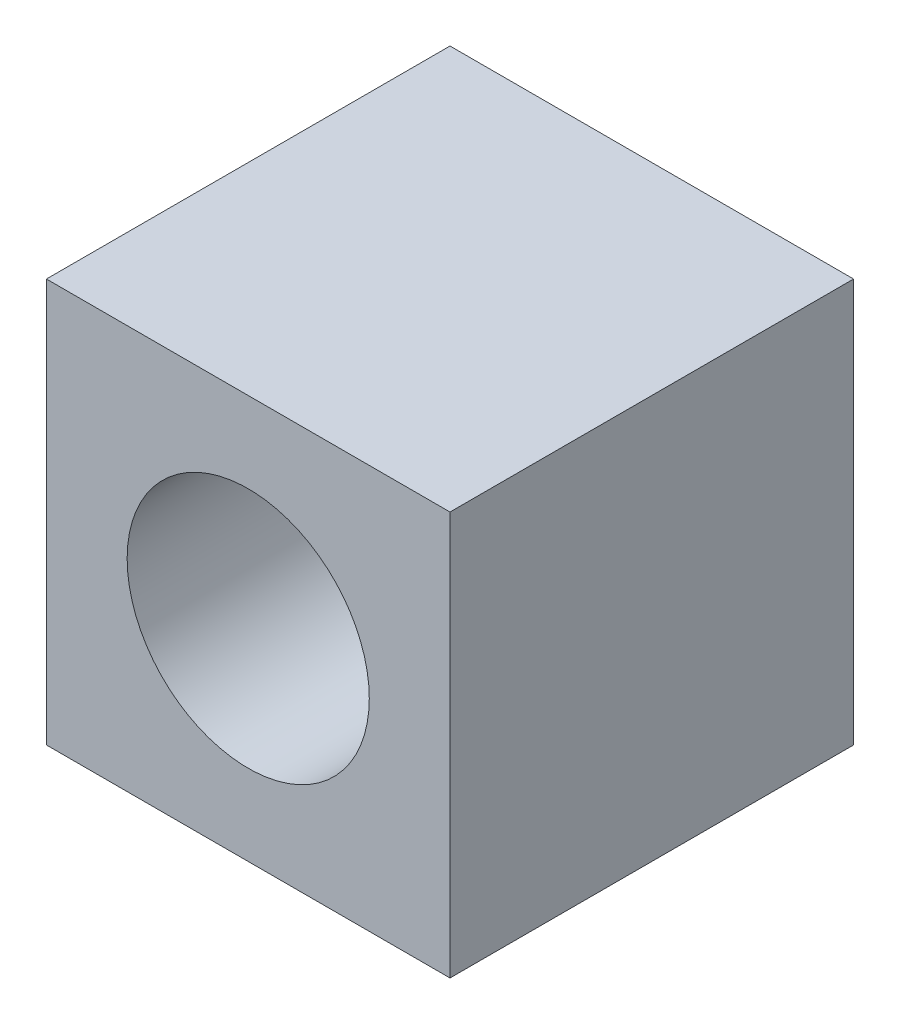
SolidWorks part; units mm, degrees
ref_plane "前视基准面" through (0, 0, 0) normal (0, 0, 1) x (1, 0, 0)
ref_plane "上视基准面" through (0, 0, 0) normal (0, 1, 0) x (1, 0, 0)
ref_plane "右视基准面" through (0, 0, 0) normal (1, 0, 0) x (0, 0, -1)
other "Configuration Table"
sketch "草图1" plane through (0, 0, 0) normal (0, 0, 1) x (1, 0, 0)
  line L1 (0, 0) -> (10, 0)
  line L2 (0, 0) -> (0, 10)
  line L3 (0, 10) -> (10, 10)
  line L4 (10, 0) -> (10, 10)
extrude "凸台-拉伸1" add sketch "草图1" along normal blind 10
sketch "草图2" plane through (0, 0, 10) normal (0, 0, 1) x (1, 0, 0)
  circle A0 centre (5, 5) radius 3
extrude "切除-拉伸1" cut sketch "草图2" against normal blind 5
